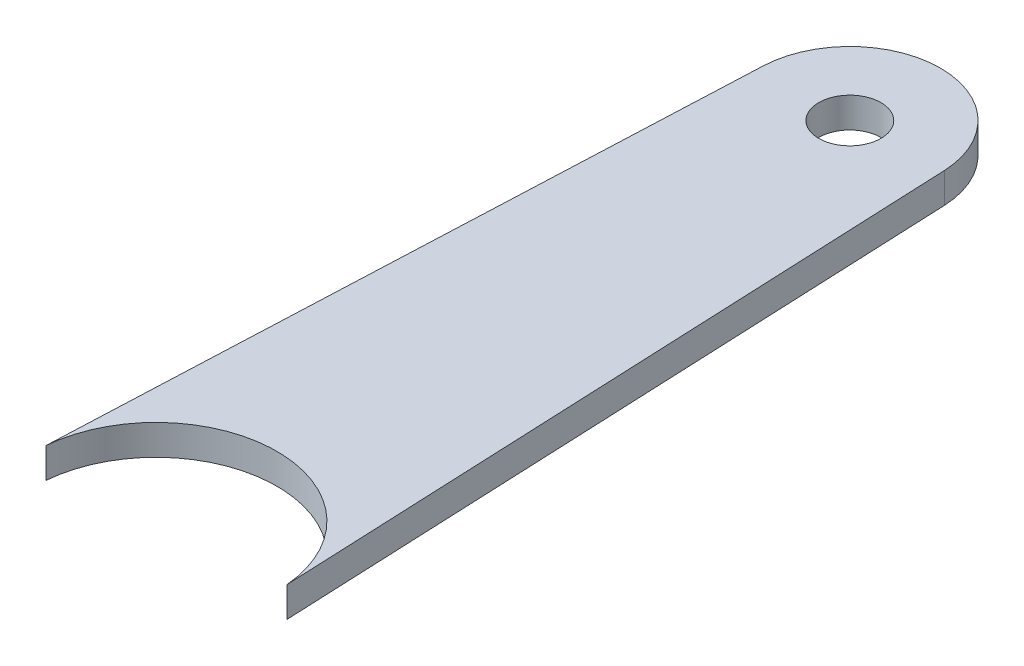
SolidWorks part; units mm, degrees
ref_plane "Front Plane" through (0, 0, 0) normal (0, 0, 1) x (1, 0, 0)
ref_plane "Top Plane" through (0, 0, 0) normal (0, 1, 0) x (1, 0, 0)
ref_plane "Right Plane" through (0, 0, 0) normal (1, 0, 0) x (0, 0, -1)
sketch "Sketch1" plane through (0, 0, 0) normal (0, 1, 0) x (1, 0, 0)
  line L0 (0, 0) -> (25.4, 0)
  line L1 (25.4, 0) -> (22.216, 73.2936)
  line L2 (0, 0) -> (3.184, 73.2936)
  line L3 (12.7, 72.8802) -> (12.7, 0) construction
  arc A0 (22.216, 73.2936) -> (3.184, 73.2936) centre (12.7, 72.8802) ccw
  circle A1 centre (12.7, 72.8802) radius 3.2639
  circle A2 centre (12.7, 0) radius 12.7
  point P6 (12.7, 0)
  dimension "D2" = 6.5278
  dimension "D3" = 9.525
  dimension "D1" = 72.8802
  dimension "D4" = 25.4
extrude "Boss-Extrude2" add sketch "Sketch1" along normal blind 3.175 contours A2 L1 A0 L2 A1
